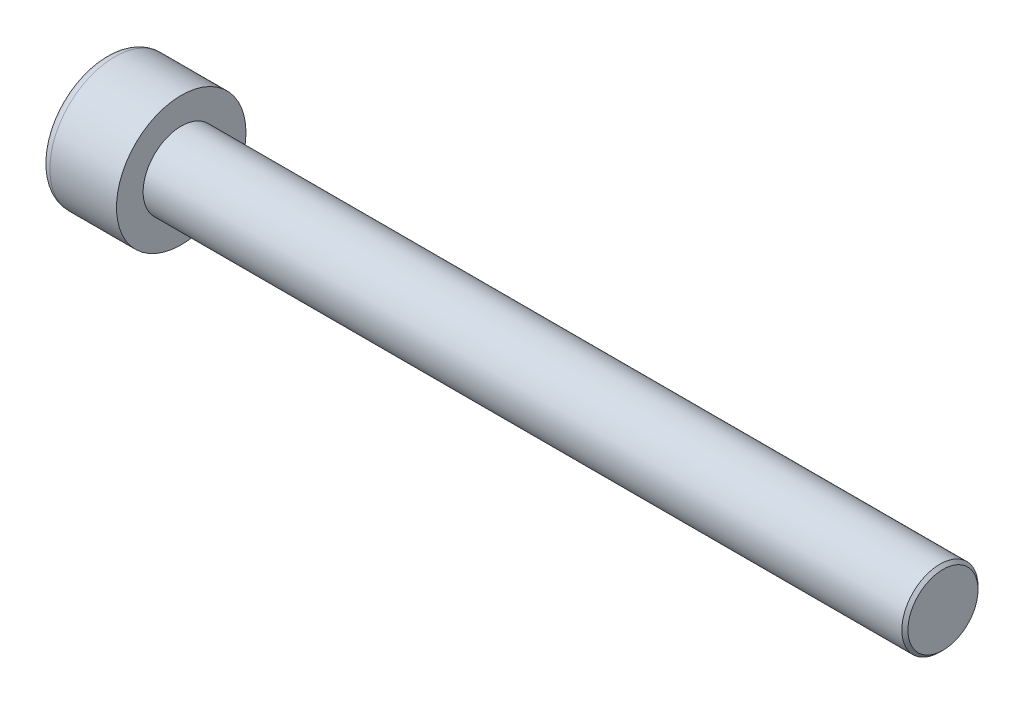
SolidWorks part; units mm, degrees
ref_plane "Front" through (0, 0, 0) normal (0, 0, 1) x (1, 0, 0)
ref_plane "Top" through (0, 0, 0) normal (0, 1, 0) x (1, 0, 0)
ref_plane "Right" through (0, 0, 0) normal (1, 0, 0) x (0, 0, -1)
sketch "Sketch1" plane through (0, 0, 0) normal (1, 0, 0) x (0, 0, -1)
  circle A0 centre (0, 0) radius 4.25
  dimension "dk" = 8.5
extrude "BaseHead" add sketch "Sketch1" along normal blind 5
sketch "Sketch2" plane through (5, 0, 0) normal (1, 0, 0) x (0, 0, -1)
  circle A0 centre (0, 0) radius 2.5
  dimension "d" = 5
extrude "BaseBody" add sketch "Sketch2" along normal blind 50
cosmetic thread "ThreadCosmetic1" parameters "b"=22, "D2"=4.134
sketch "Sketch3" plane through (0, 0, 0) normal (1, 0, 0) x (0, 0, -1)
  line L1 (2.3094, 0) -> (1.1547, 2)
  line L2 (1.1547, 2) -> (-1.1547, 2)
  line L3 (-1.1547, 2) -> (-2.3094, 0)
  line L4 (-2.3094, 0) -> (-1.1547, -2)
  line L5 (-1.1547, -2) -> (1.1547, -2)
  line L6 (1.1547, -2) -> (2.3094, 0)
  circle A0 centre (0, 0) radius 2 construction
  dimension "s" = 4
  dimension "e" = 4.6188
extrude "HexagonSocket" cut sketch "Sketch3" along normal blind 2.5
sketch "Sketch4" plane through (-4.1961, 0.75, 0) normal (0, 0, 1) x (-1, 0, 0)
  line L0 (-6.6961, 2.75) -> (-7.8508, 0.75)
  line L2 (-7.8508, 0.75) -> (-6.6961, 0.75)
  line L3 (-6.6961, 0.75) -> (-6.6961, 2.75)
  line L4 (-5.0351, 0.75) -> (0.839, 0.75) construction
  line L5 (-59.1961, 0.75) -> (-9.1961, 0.75) construction
  line L6 (-9.1961, 0.75) -> (-4.1961, 0.75) construction
  dimension "m" = 60
revolve "Cut-Revolve1" cut sketch "Sketch4" angle 360 about L4
fillet "HeadFillet" [suppressed] radius 0.2
fillet "TopFillet" radius 0.625 1 edges at (0, 0, -4.25)
chamfer "Chamfer1" distance 0.2 angle 45 1 edges at (55, 0, -2.5)
sketch "Sketch5" plane through (0, 0, 0) normal (0, 0, 1) x (1, 0, 0)
  line L0 (54.8, 2.125) -> (55.0165, 2.5)
  line L1 (55.0165, 2.5) -> (55.0165, 2.933)
  line L2 (55.0165, 2.933) -> (54.5835, 2.933)
  line L3 (54.5835, 2.933) -> (54.5835, 2.5)
  line L4 (54.5835, 2.5) -> (54.8, 2.125)
  line L5 (0, 0) -> (7.8886, 0) construction
  line L6 (54.8, -2.5) -> (54.8, 2.5) construction
  dimension "D1" = 5
  dimension "D2" = 0.433
revolve "Cut-Revolve10" [suppressed] cut sketch "Sketch5" angle 360 about L5
pattern_linear "LPattern10" [suppressed] count 42 spacing 0.5196 along (1, 0, 0)
equation "\"r1@TopFillet\" = \"d@Sketch2\" / 8"
equation "\"D1@Chamfer1\" = \"r@HeadFillet\""
equation "\"D1@Sketch5\" = \"d@Sketch2\""
equation "\"D2@Sketch5\" =  ( \"d@Sketch2\" - \"D2@ThreadCosmetic1\" )  / 2"
equation "\"D3@LPattern10\" = \"D2@Sketch5\" * 1.2"
equation "\"D1@LPattern10\" = \"b@ThreadCosmetic1\" / \"D3@LPattern10\""
